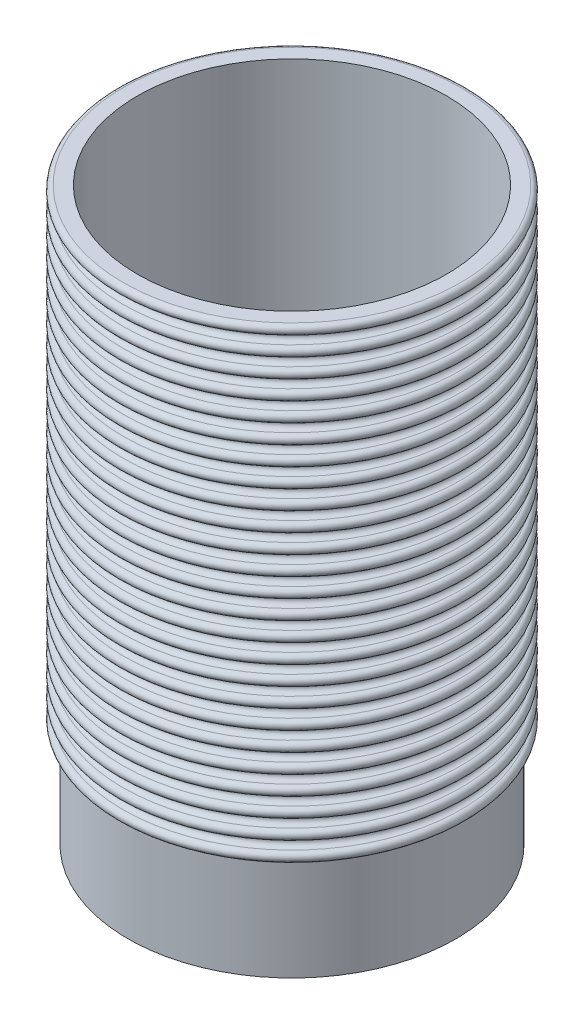
SolidWorks part; units mm, degrees
material "Gray Cast Iron"
ref_plane "Front Plane" through (0, 0, 0) normal (0, 0, 1) x (1, 0, 0)
ref_plane "Top Plane" through (0, 0, 0) normal (0, 1, 0) x (1, 0, 0)
ref_plane "Right Plane" through (0, 0, 0) normal (1, 0, 0) x (0, 0, -1)
sketch "Sketch1" plane through (0, 0, 0) normal (0, 1, 0) x (1, 0, 0)
  circle A0 centre (0, 0) radius 51.5938
  circle A1 centre (0, 0) radius 54.7688
  dimension "D1" = 103.1875
  dimension "D2" = 3.175
extrude "Boss-Extrude1" add sketch "Sketch1" along normal blind 190.5
sketch "Sketch2" plane through (0, 0, 0) normal (0, 0, 1) x (1, 0, 0)
  line L0 (-54.7688, 0) -> (54.7688, 0) construction
  line L1 (-54.7688, 0) -> (54.7688, 0) construction
  line L2 (-54.7688, 0) -> (-54.7688, 190.5) construction
  line L3 (-54.7688, 190.5) -> (-56.3563, 190.5)
  line L4 (-56.3563, 184.15) -> (-54.7688, 184.15)
  line L5 (-54.7688, 184.15) -> (-54.7688, 190.5)
  line L6 (0, 0) -> (0, 158.75) construction
  arc A0 (-56.3563, 190.5) -> (-56.3563, 187.325) centre (-56.3563, 188.9125) ccw
  arc A1 (-56.3563, 187.325) -> (-56.3563, 184.15) centre (-56.3562, 185.7375) cw
  dimension "D1" = 1.5875
  dimension "D3" = 1.5875
  dimension "D2" = 1.5875
revolve "Revolve1" add sketch "Sketch2" angle 360 about L6
pattern_linear "LPattern1" count 24 spacing 6.35 along (0, -1, 0) of "Revolve1"
sketch "Sketch3" plane through (0, 0, 0) normal (0, 0, 1) x (1, 0, 0)
  line L0 (-54.7688, 0) -> (54.7688, 0) construction
  line L1 (-54.7688, 0) -> (54.7688, 0) construction
  line L2 (-54.7688, 0) -> (-54.7688, 38.1) construction
  line L3 (-56.3563, 38.1) -> (56.3563, 38.1) construction
  line L4 (-56.3563, 38.1) -> (56.3563, 38.1) construction
  line L5 (-56.3563, 38.1) -> (-54.7688, 38.1)
  line L6 (-54.7688, 38.1) -> (-54.7688, 33.3375)
  line L7 (0, 0) -> (0, 199.2757) construction
  arc A0 (-56.3563, 38.1) -> (-56.3563, 34.925) centre (-56.3563, 36.5125) ccw
  arc A2 (-56.3563, 34.925) -> (-54.7688, 33.3375) centre (-56.3562, 33.3375) cw
  dimension "D1" = 1.5875
revolve "Revolve2" add sketch "Sketch3" angle 360 about L7
